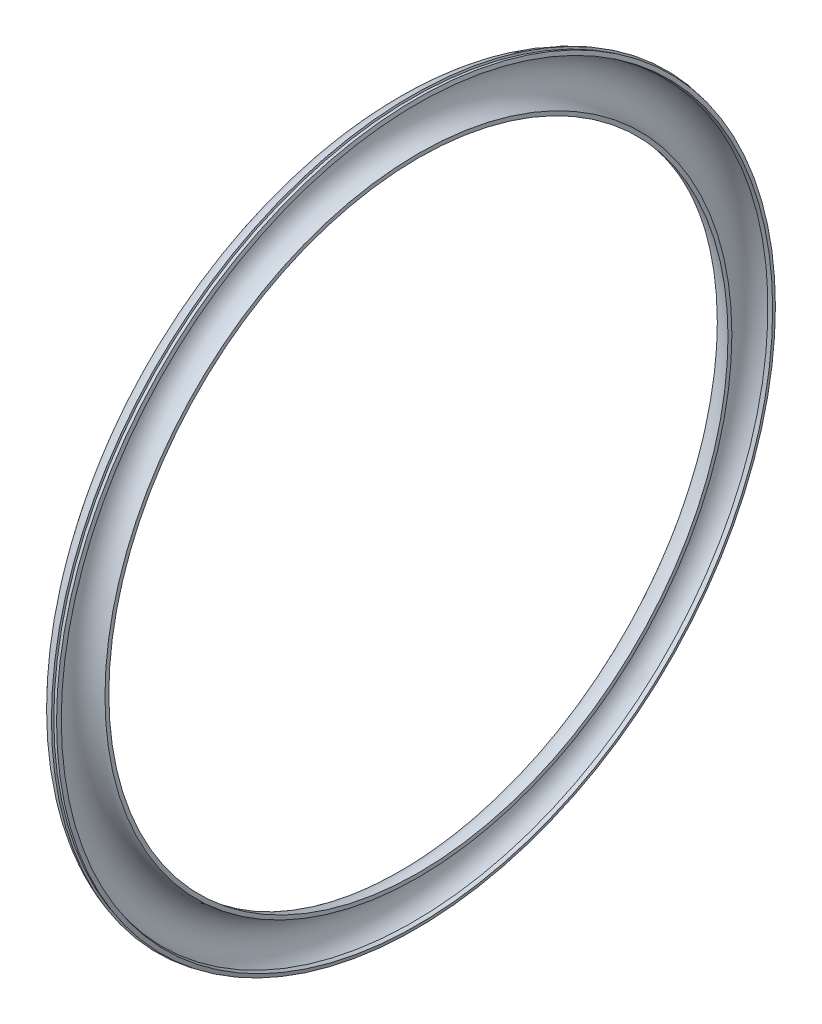
SolidWorks part; units mm, degrees
ref_plane "Front Plane" through (0, 0, 0) normal (0, 0, 1) x (1, 0, 0)
ref_plane "Top Plane" through (0, 0, 0) normal (0, 1, 0) x (1, 0, 0)
ref_plane "Right Plane" through (0, 0, 0) normal (1, 0, 0) x (0, 0, -1)
sketch "Sketch1" plane through (0, 0, 0) normal (0, 0, 1) x (1, 0, 0)
  line L0 (-136.0708, 0) -> (0, 0) construction
  line L1 (0, 0) -> (0, 260) construction
  line L2 (0, 260) -> (-4.3999, 276.4207) construction
  line L3 (-4.7882, 277.8696) -> (-1.8904, 278.6461)
  line L4 (-1.8904, 278.6461) -> (-1.1139, 275.7483)
  line L5 (-1.1139, 275.7483) -> (-4.0117, 274.9719)
  line L6 (-4.0117, 274.9719) -> (-4.3999, 276.4207)
  line L7 (0, 243) -> (0, 240)
  line L8 (-4.7882, 277.8696) -> (-5.1764, 279.3185)
  line L9 (-4.7882, 277.8696) -> (-13.146, 309.0615) construction
  arc A0 (0, 240) -> (-5.1764, 279.3185) centre (0, 260) cw
  arc A1 (0, 243) -> (-4.3999, 276.4207) centre (0, 260) cw
  arc A2 (0, 240) -> (0, 280) centre (0, 260) cw construction
  arc A4 (0, 243) -> (0, 277) centre (0, 260) cw construction
  dimension "D2" = 20
  dimension "D3" = 17
  dimension "D1" = 260
  dimension "D4" = 15
  dimension "D5" = 18.5
  dimension "D6" = 3
  dimension "D7" = 3
revolve "Revolve1" add sketch "Sketch1" angle 360 about L0
